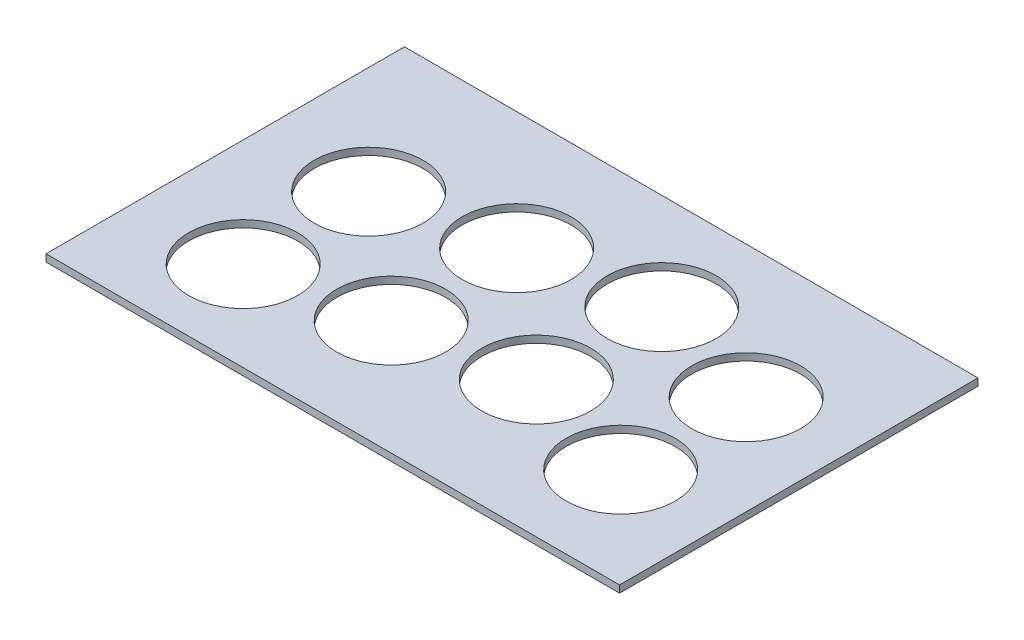
SolidWorks part; units mm, degrees
ref_plane "Front Plane" through (0, 0, 0) normal (0, 0, 1) x (1, 0, 0)
ref_plane "Top Plane" through (0, 0, 0) normal (0, 1, 0) x (1, 0, 0)
ref_plane "Right Plane" through (0, 0, 0) normal (1, 0, 0) x (0, 0, -1)
sketch "Sketch1" plane through (0, 0, 0) normal (0, 1, 0) x (1, 0, 0)
  line L0 (-130, -40) -> (-95.7071, -33) construction
  line L1 (0, 0) -> (-160, 0)
  line L2 (0, 0) -> (0, -100)
  line L3 (0, -100) -> (-160, -100)
  line L4 (-160, 0) -> (-160, -100)
  line L5 (-95.7071, -33) -> (-61.2253, -27) construction
  line L6 (-61.2253, -27) -> (-27.6842, -37) construction
  line L7 (-27.6842, -37) -> (-27.6842, -72) construction
  line L8 (-27.6842, -72) -> (-61.2253, -62) construction
  line L9 (-61.2253, -62) -> (-95.7071, -68) construction
  line L10 (-95.7071, -68) -> (-130, -75) construction
  line L11 (-130, -75) -> (-130, -40) construction
  line L12 (-95.7071, -68) -> (-95.7071, -33) construction
  line L13 (-61.2253, -62) -> (-61.2253, -27) construction
  line L14 (-27.6842, -37) -> (-27.6842, -27) construction
  line L15 (-27.6842, -27) -> (-61.2253, -27) construction
  line L16 (-61.2253, -27) -> (-95.7071, -27) construction
  line L17 (-95.7071, -33) -> (-95.7071, -27) construction
  line L18 (-95.7071, -33) -> (-130, -33) construction
  line L19 (-130, -33) -> (-130, -40) construction
  line L20 (-130, -40) -> (-160, -40) construction
  line L21 (-130, -40) -> (-130, 0) construction
  circle A16 centre (-130, -40) radius 15 construction
  circle A17 centre (-95.7071, -33) radius 15 construction
  circle A18 centre (-61.2253, -27) radius 15 construction
  circle A19 centre (-27.6842, -37) radius 15 construction
  circle A20 centre (-130, -75) radius 15 construction
  circle A21 centre (-95.7071, -68) radius 15 construction
  circle A22 centre (-61.2253, -62) radius 15 construction
  circle A23 centre (-27.6842, -72) radius 15 construction
  circle A24 centre (-130, -40) radius 15.2
  circle A25 centre (-95.7071, -33) radius 15.2
  circle A26 centre (-61.2253, -27) radius 15.2
  circle A27 centre (-27.6842, -37) radius 15.2
  circle A28 centre (-27.6842, -72) radius 15.2
  circle A29 centre (-61.2253, -62) radius 15.2
  circle A30 centre (-95.7071, -68) radius 15.2
  circle A31 centre (-130, -75) radius 15.2
  point P42 (-69.038, -62)
  dimension "D1" = 30
  dimension "D3" = 10
  dimension "D4" = 6
  dimension "D5" = 7
  dimension "D6" = 40
  dimension "D7" = 30
  dimension "D8" = 0.2
  dimension "D2" = 35
  dimension "D9" = 100
  dimension "D10" = 160
extrude "Boss-Extrude1" add sketch "Sketch1" along normal blind 2
